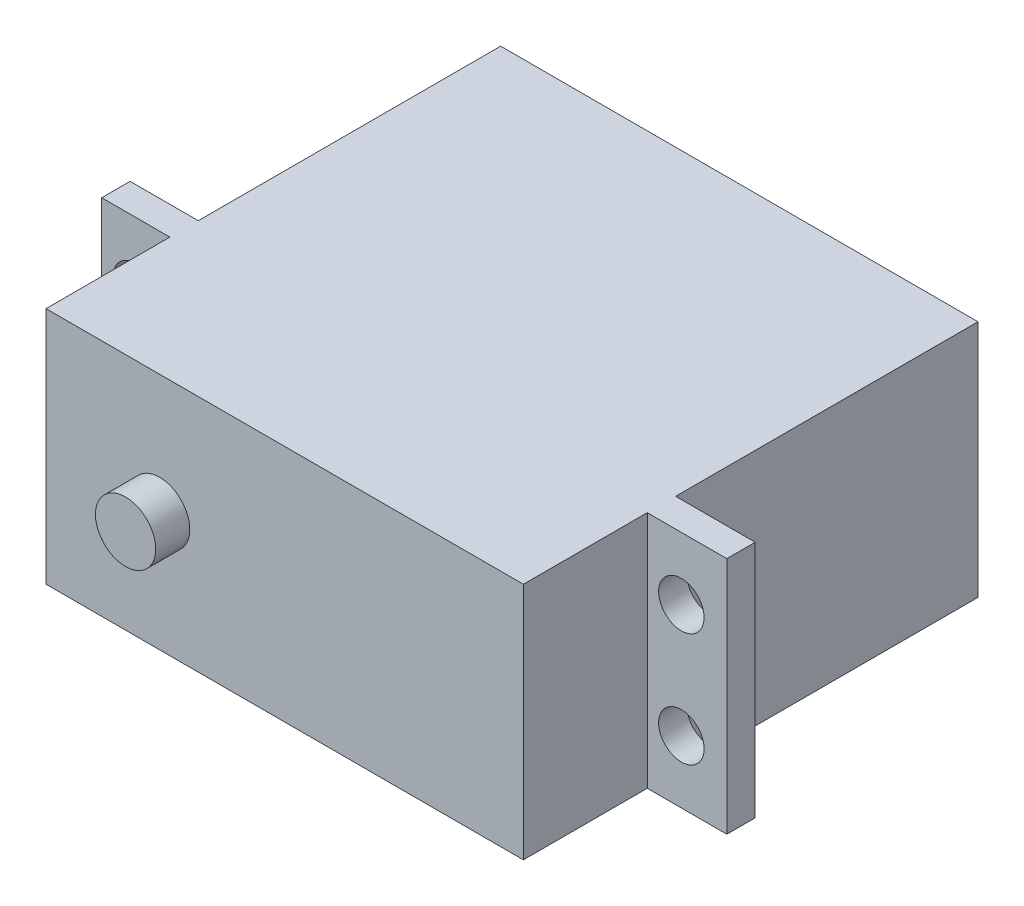
SolidWorks part; units mm, degrees
ref_plane "Plan de face" through (0, 0, 0) normal (0, 0, 1) x (1, 0, 0)
ref_plane "Plan de dessus" through (0, 0, 0) normal (0, 1, 0) x (1, 0, 0)
ref_plane "Plan de droite" through (0, 0, 0) normal (1, 0, 0) x (0, 0, -1)
sketch "Esquisse1" plane through (0, 0, 0) normal (0, 0, 1) x (1, 0, 0)
  line L1 (-10, -10.5) -> (32, -10.5)
  line L2 (-10, -10.5) -> (-10, 10.5)
  line L3 (-10, 10.5) -> (32, 10.5)
  line L4 (32, -10.5) -> (32, 10.5)
  point P5 (-10, 0)
  dimension "D1" = 21
  dimension "D2" = 42
  dimension "D3" = 10
extrude "Boss.-Extru.1" add sketch "Esquisse1" against normal blind 40
sketch "Esquisse2" plane through (32, 0, 0) normal (1, 0, 0) x (0, 0, -1)
  line L0 (40, 10.5) -> (0, 10.5) construction
  line L1 (13.4, 10.5) -> (10.9, 10.5)
  line L2 (13.4, 10.5) -> (13.4, -10.5)
  line L3 (13.4, -10.5) -> (10.9, -10.5)
  line L4 (10.9, 10.5) -> (10.9, -10.5)
  line L5 (40, -10.5) -> (0, -10.5) construction
  line L7 (40, -10.5) -> (40, 10.5) construction
  dimension "D1" = 2.5
  dimension "D2" = 26.6
extrude "Boss.-Extru.2" add sketch "Esquisse2" along normal blind 7 and the other way blind 48
sketch "Esquisse3" plane through (0, 0, -13.4) normal (0, 0, -1) x (-1, 0, 0)
  line L0 (-32, 0) -> (10, 0) construction
  line L3 (-11, 0) -> (-11, 10.5) construction
  line L5 (-32, -10.5) -> (-32, 10.5) construction
  line L6 (10, 10.5) -> (10, -10.5) construction
  line L7 (-32, 10.5) -> (10, 10.5) construction
  circle A0 centre (13, 5) radius 2
  circle A1 centre (13, -5) radius 2
  circle A2 centre (-35, -5) radius 2
  circle A3 centre (-35, 5) radius 2
  point P9 (-11, 0)
  dimension "D1" = 24
  dimension "D3" = 5
extrude "Enlèv. mat.-Extru.1" cut sketch "Esquisse3" against normal blind 7.5
sketch "Esquisse5" plane through (0, 0, 0) normal (0, 0, -1) x (-1, 0, 0)
  circle A0 centre (0, 0) radius 2.65
  dimension "D2" = 5.3
extrude "Boss.-Extru.3" add sketch "Esquisse5" against normal blind 3
